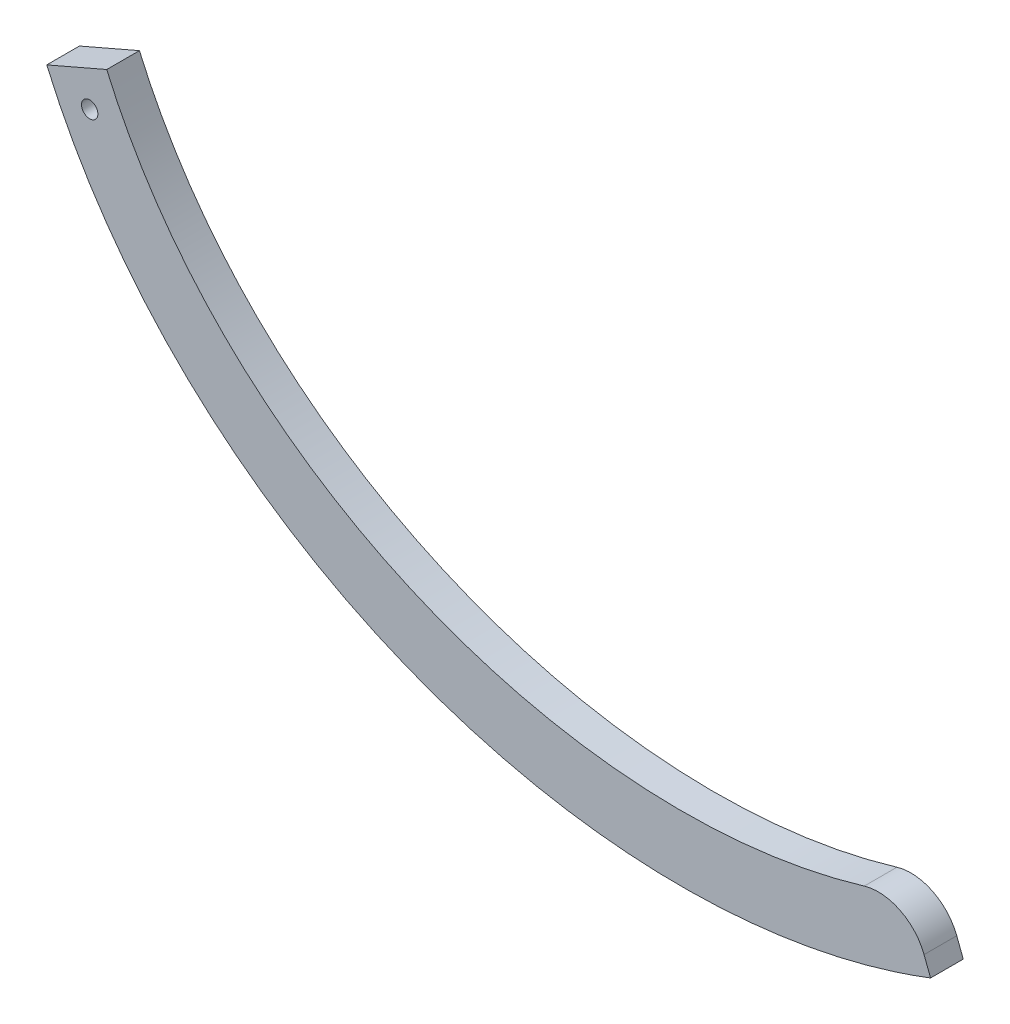
SolidWorks part; units mm, degrees
ref_plane "Front Plane" through (0, 0, 0) normal (0, 0, 1) x (1, 0, 0)
ref_plane "Top Plane" through (0, 0, 0) normal (0, 1, 0) x (1, 0, 0)
ref_plane "Right Plane" through (0, 0, 0) normal (1, 0, 0) x (0, 0, -1)
sketch "Sketch1" plane through (0, 0, 0) normal (0, 0, 1) x (1, 0, 0)
  line L0 (-134.8575, 72.1715) -> (142.1429, 72.1715) construction
  line L1 (-69.8575, -3.8219) -> (129.4448, -3.8219) construction
  line L2 (-153.2098, 64.2223) -> (-134.8575, 72.1715)
  line L3 (117.1568, -42.4969) -> (109.9981, -23.8219)
  line L4 (-140.0664, 59.0175) -> (-144.0337, 68.1969) construction
  circle A0 centre (-140.0664, 59.0175) radius 2.5
  spline S0 degree 3 poles (-134.8575, 72.1715) (-95.1128, -19.587) (19.68, -58.4437) (109.9981, -23.8219) knots 0 0 0 0 1 1 1 1
  spline S1 degree 1 poles (-153.2098, 64.2223) (117.1568, -42.4969) knots 0 0 1 1 construction
  spline S2 degree 3 poles (-153.2098, 64.2223) (-151.8265, 61.0285) (-148.8687, 54.6946) (-142.3497, 42.5564) (-133.0661, 28.259) (-120.3142, 12.6025) (-106.1296, -1.5248) (-90.6918, -14.0905) (-68.6631, -28.7345) (-38.8269, -43.0369) (-0.5601, -53.6467) (32.4261, -56.8606) (58.9039, -55.9169) (78.6591, -53.4101) (94.9133, -49.7839) (107.705, -45.9404) (114.029, -43.6958) (117.1568, -42.4969) knots 0 0 0 0 0.03125 0.0625 0.125 0.1875 0.25 0.3125 0.375 0.5 0.625 0.75 0.8125 0.875 0.9375 0.96875 1 1 1 1
  dimension "D7" = 5
  dimension "D8" = 10
  dimension "D1" = 263
  dimension "D2" = 100
  dimension "D3" = 65
  dimension "D4" = 30
  dimension "D5" = 20
  dimension "D6" = 20
extrude "Boss-Extrude1" add sketch "Sketch1" along normal blind 10
fillet "Fillet1" radius 15 1 edges at (109.9981, -23.8219, 5)
